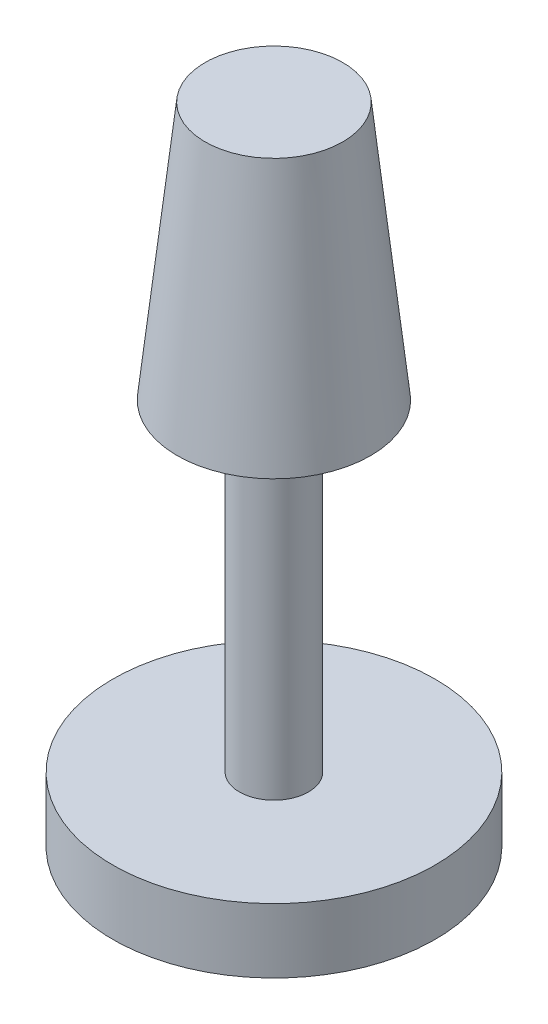
SolidWorks part; units mm, degrees
ref_plane "Front Plane" through (0, 0, 0) normal (0, 0, 1) x (1, 0, 0)
ref_plane "Top Plane" through (0, 0, 0) normal (0, 1, 0) x (1, 0, 0)
ref_plane "Right Plane" through (0, 0, 0) normal (1, 0, 0) x (0, 0, -1)
sketch "Sketch1" plane through (0, 0, 0) normal (0, 0, 1) x (1, 0, 0)
  line L0 (0, -8.6472) -> (0, 11.3528)
  line L1 (0, 11.3528) -> (2.135, 11.3528)
  line L3 (1.0717, -8.6472) -> (0, -8.6472)
  line L5 (1.0717, 3.3528) -> (1.0717, -8.6472)
  line L7 (2.135, 11.3528) -> (3, 3.3528)
  line L8 (3, 3.3528) -> (1.0717, 3.3528)
  point P5 (0, 0)
  point P6 (0, 0)
  point P8 (0, 0)
  point P9 (0, 0)
  point P10 (2.135, -8.3896)
  point P11 (0, 0)
  point P12 (0, 0)
  point P14 (0, 0)
  point P15 (0, 0)
  point P16 (0, 0)
  point P17 (0, 0)
  point P18 (0, 0)
  point P19 (0, 0)
  point P20 (0, 0)
  point P21 (0, 0)
  point P22 (0, 0)
  point P23 (0, 0)
  point P24 (0, 0)
  point P25 (0, 0)
  dimension "D1" = 20
  dimension "D2" = 2.135
  dimension "D3" = 8
  dimension "D4" = 3
revolve "Revolve2" add sketch "Sketch1" angle 360 about L0
sketch "Sketch3" plane through (0, 0, 0) normal (0, 0, 1) x (1, 0, 0)
  line L0 (-1.0717, -8.6472) -> (1.0717, -8.6472) construction
  line L1 (0, -8.6472) -> (5, -8.6472)
  line L2 (0, -8.6472) -> (0, -6.6472)
  line L3 (0, -6.6472) -> (5, -6.6472)
  line L4 (5, -8.6472) -> (5, -6.6472)
  dimension "D1" = 5
  dimension "D2" = 2
revolve "Revolve3" add sketch "Sketch3" angle 360 about L2
